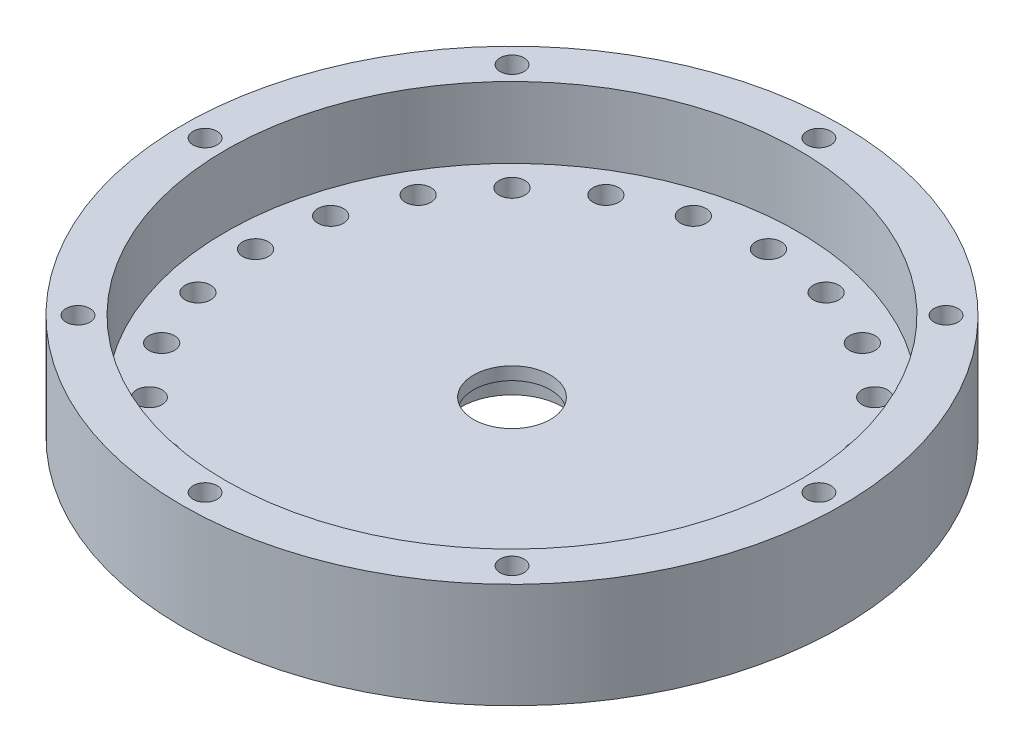
SolidWorks part; units mm, degrees
ref_plane "Front Plane" through (0, 0, 0) normal (0, 0, 1) x (1, 0, 0)
ref_plane "Top Plane" through (0, 0, 0) normal (0, 1, 0) x (1, 0, 0)
ref_plane "Right Plane" through (0, 0, 0) normal (1, 0, 0) x (0, 0, -1)
sketch "Sketch1" plane through (0, 0, 0) normal (0, 1, 0) x (1, 0, 0)
  circle A0 centre (0, 0) radius 77.1
extrude "Boss-Extrude1" add sketch "Sketch1" along normal blind 24.6
sketch "Sketch2" plane through (0, 24.6, 0) normal (0, 1, 0) x (1, 0, 0)
  circle A0 centre (0, 0) radius 67
  dimension "D1" = 134
extrude "Cut-Extrude1" cut sketch "Sketch2" against normal blind 16.6
sketch "Sketch3" plane through (0, 8, 0) normal (0, 1, 0) x (1, 0, 0)
  circle A1 centre (60, 0) radius 3
  circle A2 centre (57.9555, -15.5291) radius 3
  circle A3 centre (51.9615, -30) radius 3
  circle A4 centre (42.4264, -42.4264) radius 3
  circle A5 centre (30, -51.9615) radius 3
  circle A6 centre (15.5291, -57.9555) radius 3
  circle A7 centre (0, -60) radius 3
  circle A8 centre (-15.5291, -57.9555) radius 3
  circle A9 centre (-30, -51.9615) radius 3
  circle A10 centre (-42.4264, -42.4264) radius 3
  circle A11 centre (-51.9615, -30) radius 3
  circle A12 centre (-57.9555, -15.5291) radius 3
  circle A13 centre (-60, 0) radius 3
  circle A14 centre (-57.9555, 15.5291) radius 3
  circle A15 centre (-51.9615, 30) radius 3
  circle A16 centre (-42.4264, 42.4264) radius 3
  circle A17 centre (-30, 51.9615) radius 3
  circle A18 centre (-15.5291, 57.9555) radius 3
  circle A19 centre (0, 60) radius 3
  circle A20 centre (15.5291, 57.9555) radius 3
  circle A21 centre (30, 51.9615) radius 3
  circle A22 centre (42.4264, 42.4264) radius 3
  circle A25 centre (51.9615, 30) radius 3
  circle A26 centre (57.9555, 15.5291) radius 3
  point P13 (0, 0)
  dimension "D1" = 6
  dimension "D2" = 60
  dimension "D3" = 24
extrude "Cut-Extrude2" cut sketch "Sketch3" against normal blind 5
sketch "Sketch4" plane through (0, 0, 0) normal (0, -1, 0) x (1, 0, 0)
  circle A0 centre (0, 0) radius 12
  dimension "D1" = 24
extrude "Cut-Extrude3" cut sketch "Sketch4" against normal blind 5
sketch "Sketch5" plane through (0, 8, 0) normal (0, 1, 0) x (1, 0, 0)
  circle A0 centre (0, 0) radius 9
  dimension "D1" = 18
extrude "Cut-Extrude4" cut sketch "Sketch5" against normal blind 5
sketch "Sketch6" plane through (0, 24.6, 0) normal (0, 1, 0) x (1, 0, 0)
  line L0 (0, 71.8) -> (0, 0) construction
  circle A0 centre (0, 71.8) radius 2.8
  circle A3 centre (50.7703, 50.7703) radius 2.8
  circle A4 centre (71.8, 0) radius 2.8
  circle A5 centre (50.7703, -50.7703) radius 2.8
  circle A6 centre (0, -71.8) radius 2.8
  circle A7 centre (-50.7703, -50.7703) radius 2.8
  circle A8 centre (-71.8, 0) radius 2.8
  circle A9 centre (-50.7703, 50.7703) radius 2.8
  point P19 (0, 0)
  dimension "D1" = 6
  dimension "D2" = 8
extrude "Cut-Extrude5" cut sketch "Sketch6" against normal blind 8
equation "\"N_pin\"= 24"
equation "\"R_pin\"= 60"
equation "\"d_pin\"= 13"
equation "\"e\"= 1.5"
equation "\"t_disk\"= 5"
equation "\"N_outpin\"= 8"
equation "\"R_outpin\"= 34"
equation "\"d_outpin\"= 13"
equation "\"N_lobes\"= \"N_pin\" - 1"
equation "\"d_outhole\"= \"d_outpin\" + 2 * \"e\""
equation "\"ratio\"= \"N_lobes\""
equation "\"d_center\"= 24"
equation "\"a_hole1\"= 0 / \"N_lobes\""
equation "\"a_hole2\"= 360 / \"N_disk\" / \"N_lobes\""
equation "\"a_hole3\"= 720 / \"N_disk\" / \"N_lobes\""
equation "\"N_disk\"= 3"
equation "\"t_gap\"= 0.5"
equation "\"L_stack\"= \"N_disk\" * \"t_disk\" + (\"N_disk\" - 1) * \"t_gap\""
equation "\"d_pinshaft\"= 6"
equation "\"d_ecc\"= 15"
equation "\"d_outbrg\"= 47"
equation "\"w_outbrg\"= 7"
equation "\"d_outshaft\"= 35"
equation "\"w_brg\"= 5"
equation "\"c_run\"= 0.5"
equation "\"c_ax\"= 0.3"
equation "\"D_pocket\"= 2 * \"R_pin\" + \"d_pin\" + 2 * \"c_run\""
equation "\"h_pocket\"= \"L_stack\" + 2 * \"c_ax\""
equation "\"t_floor\"= 8"
equation "\"d_insert\"= 5.6"
equation "\"N_bolt\"= 8"
equation "\"R_bolt\"= \"D_pocket\" / 2 + 2 + \"d_insert\" / 2"
equation "\"D_housing\"= 2 * (\"R_bolt\" + \"d_insert\" / 2 + 2.5)"
equation "\"D1@Sketch1\"=\"D_housing\""
equation "\"D1@Boss-Extrude1\"=\"t_floor\"+\"h_pocket\""
equation "\"D1@Sketch2\"=\"D_pocket\""
equation "\"D1@Cut-Extrude1\"=\"h_pocket\""
equation "\"D1@Sketch3\"=\"d_pinshaft\""
equation "\"D2@Sketch3\"=\"R_pin\""
equation "\"D1@Cut-Extrude2\"=\"t_floor\"-3"
equation "\"D3@Sketch3\"=\"N_pin\""
equation "\"D1@Sketch4\"=\"d_center\""
equation "\"D1@Cut-Extrude3\"=\"w_brg\""
equation "\"D1@Sketch5\"=\"d_ecc\"+3"
equation "\"D1@Sketch6\"=\"d_insert\""
equation "\"D2@Sketch6\"=\"N_bolt\""
equation "\"D3@Sketch6\"=\"R_bolt\""
